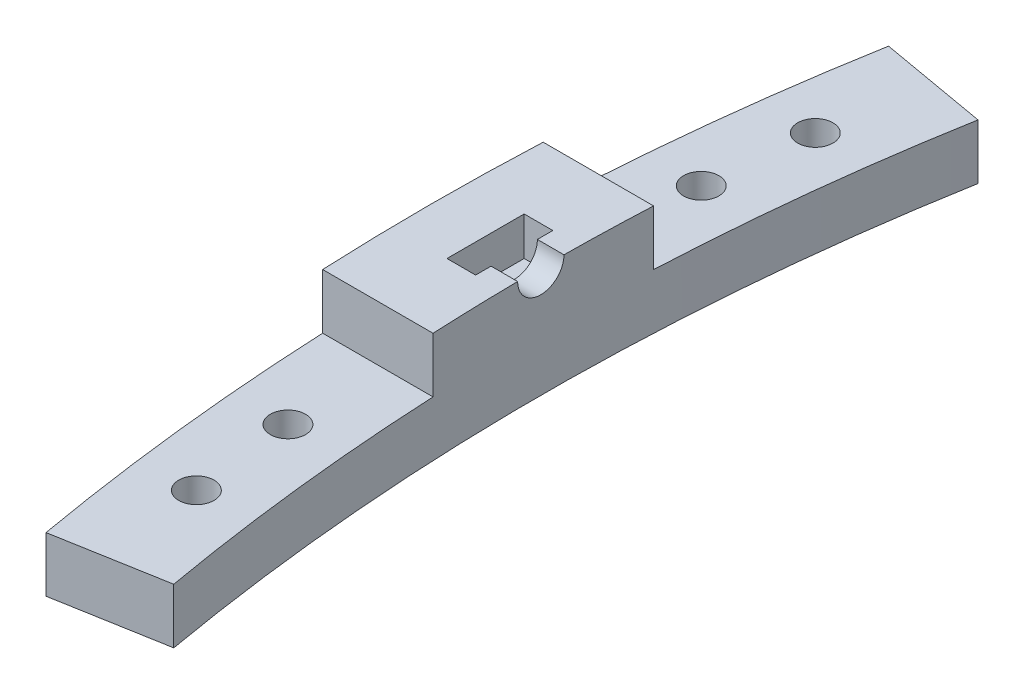
SolidWorks part; units mm, degrees
ref_plane "Front Plane" through (0, 0, 0) normal (0, 0, 1) x (1, 0, 0)
ref_plane "Top Plane" through (0, 0, 0) normal (0, 1, 0) x (1, 0, 0)
ref_plane "Right Plane" through (0, 0, 0) normal (1, 0, 0) x (0, 0, -1)
sketch "Sketch1" plane through (0, 0, 0) normal (0, 1, 0) x (1, 0, 0)
  line L0 (0, 0) -> (-216.6577, -38.2026) construction
  line L1 (0, 0) -> (-216.6577, 38.2026) construction
  line L2 (0, 0) -> (-215, 0) construction
  line L3 (-216.6577, 38.2026) -> (-206.8096, 36.4661)
  line L4 (-206.8096, -36.4661) -> (-216.6577, -38.2026)
  arc A0 (-216.6577, 38.2026) -> (-216.6577, -38.2026) centre (0, 0) ccw
  arc A1 (-206.8096, 36.4661) -> (-206.8096, -36.4661) centre (0, 0) ccw
  arc A2 (-211.7337, -37.3344) -> (-211.7337, 37.3344) centre (0, 0) cw construction
  dimension "D1" = 220
  dimension "D2" = 210
  dimension "D3" = 5
  dimension "D4" = 20
extrude "Boss-Extrude1" add sketch "Sketch1" along normal blind 5
sketch "Sketch2" [suppressed] plane through (0, 7.5, 0) normal (0, 1, 0) x (1, 0, 0)
  line L2 (0, 0) -> (-215, 0) construction
  line L3 (0, 0) -> (-219.1197, -38.6367) construction
  line L4 (0, 0) -> (-219.1197, 38.6367) construction
  line L5 (0, 0) -> (-210, 0) construction
  line L6 (0, 0) -> (-219.1197, -38.6367) construction
  line L7 (0, 0) -> (-219.1197, 38.6367) construction
  line L8 (0, 10) -> (-222.2752, 10) construction
  line L9 (0, 10) -> (0, -10) construction
  line L10 (0, -10) -> (-222.2752, -10) construction
  line L11 (-216.6577, 38.2026) -> (-206.8096, 36.4661)
  line L12 (-216.6577, -38.2026) -> (-206.8096, -36.4661)
  line L13 (-219.7726, -10) -> (-209.7618, -10)
  line L14 (-209.7618, 10) -> (-219.7726, 10)
  arc A0 (-216.6577, 38.2026) -> (-216.6577, -38.2026) centre (0, 0) ccw construction
  arc A1 (-206.8096, 36.4661) -> (-206.8096, -36.4661) centre (0, 0) ccw construction
  arc A2 (-216.6577, 38.2026) -> (-216.6577, -38.2026) centre (0, 0) ccw
  arc A3 (-206.8096, 36.4661) -> (-206.8096, -36.4661) centre (0, 0) ccw
  arc A4 (-219.1197, 38.6367) -> (-219.1197, -38.6367) centre (0, 0) ccw construction
  line M2 (-219.1197, -38.6367) -> (-204.3476, -36.032)
  line M4 (-204.3476, 36.032) -> (-219.1197, 38.6367)
  dimension "D1" = 20
extrude "Cut-Extrude1" [suppressed] cut sketch "Sketch2" against normal blind 1.5 contours A3 A2 L14 M4 | A3 L13 A2 M2
ref_plane "Plane1" through (-215, 0, 0) normal (1, 0, 0) x (0, 0, -1)
sketch "Sketch6" plane through (0, 0, 0) normal (0, -1, 0) x (1, 0, 0)
  line L0 (0, 0) -> (-214.1819, 18.7385) construction
  line L1 (0, 0) -> (-215, 0) construction
  line L2 (0, 0) -> (-215, 0) construction
  line L3 (0, 0) -> (-214.1819, -18.7385) construction
  line L4 (0, 0) -> (-213.1606, 28.0631) construction
  line L5 (0, 0) -> (-213.1606, -28.0631) construction
  arc A0 (-211.7337, 37.3344) -> (-211.7337, -37.3344) centre (0, 0) ccw construction
  dimension "D1" = 5
  dimension "D2" = 7.5
hole_wizard "Ø3.2 (3.2) Diameter Hole1" positions "Sketch7" profile "Sketch8" hole size "Ø3.2" standard "ISO" end condition through all
sketch "Sketch7" plane through (0, 0, 0) normal (0, -1, 0) x (-1, 0, 0)
  point P0 (214.1819, -18.7385)
  point P3 (214.1819, 18.7385)
  point P6 (213.1606, -28.0631)
  point P9 (213.1606, 28.0631)
sketch "Sketch8" plane through (-214.1819, 0, 18.7385) normal (1, 0, 0) x (0, 0, -1)
  line L0 (0, 0) -> (0, 5)
  line L1 (0, 5) -> (1.6, 5)
  line L2 (1.6, 5) -> (1.6, 0)
  line L5 (1.6, 0) -> (0, 0)
  line L11 (0, -6.35) -> (0, 107.95) construction
  dimension "Thru Hole Dia." = 3.2
  dimension "Thru Hole Depth" = 5
sketch "Sketch9" plane through (0, 5, 0) normal (0, 1, 0) x (1, 0, 0)
  line L0 (0, 0) -> (-215, 0) construction
  line L1 (0, 0) -> (-215, 0) construction
  line L2 (0, 10) -> (0, -10) construction
  line L3 (-219.7726, 10) -> (-209.7618, 10)
  line L4 (-219.7726, -10) -> (-209.7618, -10)
  arc A0 (-216.6577, 38.2026) -> (-216.6577, -38.2026) centre (0, 0) ccw construction
  arc A1 (-206.8096, 36.4661) -> (-206.8096, -36.4661) centre (0, 0) ccw construction
  arc A2 (-209.7618, 10) -> (-209.7618, -10) centre (0, 0) ccw
  arc A3 (-219.7726, 10) -> (-219.7726, -10) centre (0, 0) ccw
  dimension "D1" = 20
extrude "Boss-Extrude2" add sketch "Sketch9" along normal blind 5
ref_plane "Plane2" through (-215, 0, 0) normal (-1, 0, 0) x (0, 0, 1)
sketch "Sketch10" plane through (-215, 0, 0) normal (-1, 0, 0) x (0, 0, 1)
  line L0 (10, 10) -> (-10, 10) construction
  line L1 (-3.5, 13.5) -> (3.5, 13.5)
  line L2 (-3.5, 13.5) -> (-3.5, 6.5)
  line L3 (-3.5, 6.5) -> (3.5, 6.5)
  line L4 (3.5, 13.5) -> (3.5, 6.5)
  line L5 (-3.5, 13.5) -> (3.5, 6.5) construction
  line L6 (-3.5, 6.5) -> (3.5, 13.5) construction
  point P0 (0, 10)
  dimension "D1" = 7
  dimension "D2" = 7
extrude "Cut-Extrude2" cut sketch "Sketch10" against normal blind 2.6
sketch "Sketch11" plane through (-215, 0, 0) normal (-1, 0, 0) x (0, 0, 1)
  line L0 (10, 10) -> (-10, 10) construction
  circle A0 centre (0, 10) radius 2.1
  dimension "D1" = 4.2
extrude "Cut-Extrude3" cut sketch "Sketch11" against normal through all
